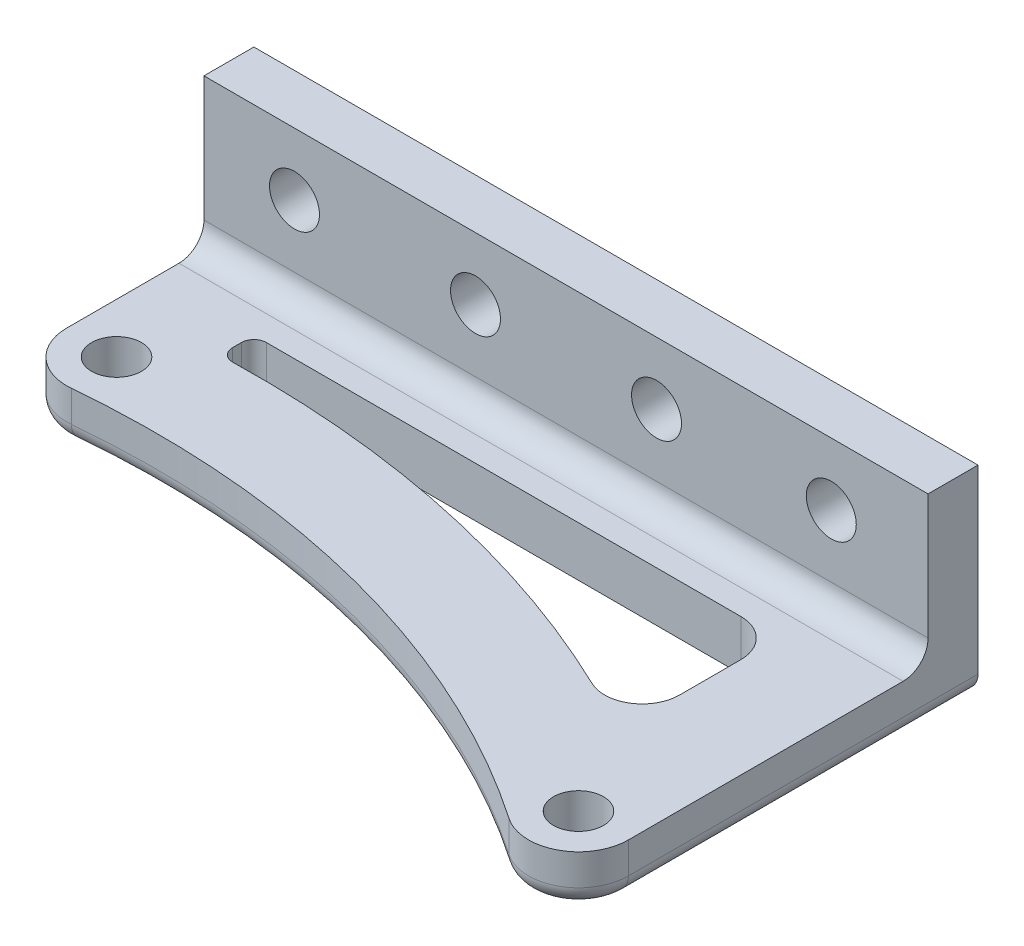
SolidWorks part; units mm, degrees
ref_plane "Front Plane" through (0, 0, 0) normal (0, 0, 1) x (1, 0, 0)
ref_plane "Top Plane" through (0, 0, 0) normal (0, 1, 0) x (1, 0, 0)
ref_plane "Right Plane" through (0, 0, 0) normal (1, 0, 0) x (0, 0, -1)
sketch "Sketch1" plane through (0, 0, 0) normal (0, 1, 0) x (1, 0, 0)
  line L3 (-4, 13) -> (-4, 28)
  line L4 (-4, 28) -> (54, 28)
  line L5 (54, 28) -> (54, 0)
  line L6 (4, 18.2898) -> (4, 19)
  line L7 (46, 12.0969) -> (46, 17)
  line L9 (25, 20) -> (43, 20)
  line L10 (25, 20) -> (5, 20)
  circle A0 centre (0, 13) radius 2
  circle A1 centre (50, 0) radius 2
  arc A4 (-4, 13) -> (0.361, 9.0163) centre (0, 13) ccw
  arc A5 (47.7444, -3.3033) -> (0.361, 9.0163) centre (6.8983, -63.1218) ccw
  arc A7 (47.7444, -3.3033) -> (54, 0) centre (50, 0) ccw
  arc A10 (5.0233, 17.2901) -> (4, 18.2898) centre (5, 18.2898) cw
  arc A11 (5, 20) -> (4, 19) centre (5, 19) ccw
  arc A12 (46, 12.0969) -> (41.7019, 9.3923) centre (43, 12.0969) cw
  arc A13 (41.7019, 9.3923) -> (5.0233, 17.2901) centre (6.8983, -63.1218) ccw
  arc A14 (46, 17) -> (43, 20) centre (43, 17) ccw
  point P0 (10.2047, -50.4051)
  point P6 (10.2047, -50.4051)
  point P7 (76.4257, -50.4051)
  point P9 (10.2047, 11.8159)
  point P12 (87.3321, -63.1218)
  point P25 (6.8983, 9.3119)
  dimension "D1" = 1
  dimension "D2" = 3
extrude "Boss-Extrude1" add sketch "Sketch1" along normal blind 4
sketch "Sketch2" plane through (0, 4, 0) normal (0, 1, 0) x (1, 0, 0)
  line L0 (-4, 28) -> (-4, 24)
  line L1 (-4, 28) -> (-4, 13) construction
  line L2 (-4, 24) -> (54, 24)
  line L3 (54, 0) -> (54, 28) construction
  line L4 (54, 24) -> (54, 28)
  line L5 (54, 28) -> (-4, 28)
extrude "Boss-Extrude2" add sketch "Sketch2" along normal blind 12
fillet "Fillet2" radius 2 1 edges at (25, 4, -24)
fillet "Fillet4" radius 1.5 5 edges at (-4, 0, -20.5) (54, 0, -14) (51.8678, 0, 3.5371) (25.1251, 0, -6.9812) (-2.6978, 0, -10.0467)
sketch "Sketch4" plane through (0, 0, -24) normal (0, 0, 1) x (1, 0, 0)
  circle A0 centre (3.25, 11) radius 2
  circle A1 centre (17.75, 11) radius 2
  circle A2 centre (32.25, 11) radius 2
  circle A3 centre (46.25, 11) radius 2
extrude "Cut-Extrude1" cut sketch "Sketch4" against normal up to surface (4 mm away) contours A1 | A2 | A3 | A0 up to face at (25, 5.7298, -28)
